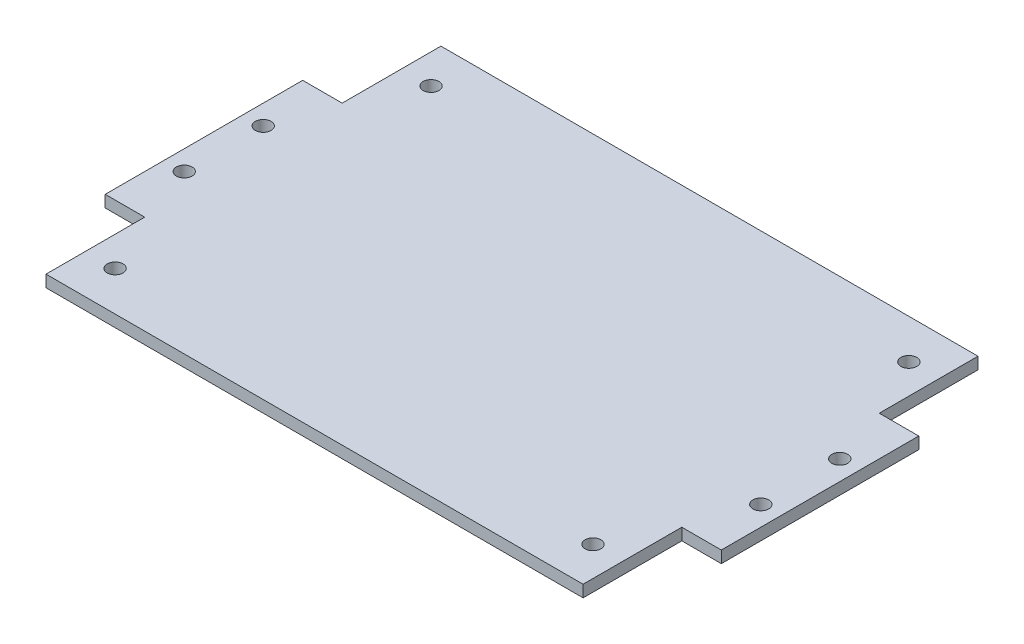
SolidWorks part; units mm, degrees
ref_plane "Plano frontal" through (0, 0, 0) normal (0, 0, 1) x (1, 0, 0)
ref_plane "Plano superior" through (0, 0, 0) normal (0, 1, 0) x (1, 0, 0)
ref_plane "Plano direito" through (0, 0, 0) normal (1, 0, 0) x (0, 0, -1)
sketch "Esboço2" plane through (0, 0, 0) normal (0, 1, 0) x (1, 0, 0)
  line L5 (-136, 100) -> (0, 100)
  line L6 (-136, 100) -> (-136, 0)
  line L7 (-136, 0) -> (0, 0)
  line L8 (0, 100) -> (0, 0)
extrude "Ressalto-extrusão1" add sketch "Esboço2" along normal blind 3
sketch "Esboço3" plane through (0, 3, 0) normal (0, 1, 0) x (1, 0, 0)
  circle A0 centre (-128.5, 10) radius 2
  circle A1 centre (-7.5, 10) radius 2
  circle A2 centre (-7.5, 90) radius 2
  circle A3 centre (-128.5, 90) radius 2
extrude "Corte-extrusão2" cut sketch "Esboço3" against normal blind 10
sketch "Esboço5" plane through (0, 0, 0) normal (1, 0, 0) x (0, 0, -1)
  line L0 (25, 0) -> (25, 3) construction
  line L1 (0, 0) -> (100, 0) construction
  line L2 (0, 3) -> (100, 3) construction
  line L3 (75, 0) -> (75, 3) construction
  line L4 (100, 3) -> (100, 0) construction
  line L5 (0, 3) -> (0, 0) construction
  line L7 (25, 0) -> (75, 0)
  line L8 (25, 0) -> (25, 3)
  line L9 (25, 3) -> (75, 3)
  line L10 (75, 0) -> (75, 3)
  dimension "D1" = 25
  dimension "D2" = 25
extrude "Ressalto-extrusão2" add sketch "Esboço5" along normal blind 10
sketch "Esboço6" plane through (-136, 0, 0) normal (-1, 0, 0) x (0, 0, 1)
  line L0 (-75, 3) -> (-75, 0) construction
  line L1 (-25, 0) -> (-25, 3) construction
  line L2 (-100, 0) -> (0, 0) construction
  line L3 (-100, 3) -> (0, 3) construction
  line L4 (-100, 3) -> (-100, 0) construction
  line L5 (0, 3) -> (0, 0) construction
  line L7 (-75, 0) -> (-25, 0)
  line L8 (-75, 0) -> (-75, 3)
  line L9 (-75, 3) -> (-25, 3)
  line L10 (-25, 0) -> (-25, 3)
  dimension "D1" = 25
  dimension "D2" = 25
extrude "Ressalto-extrusão3" add sketch "Esboço6" along normal blind 10
sketch "Esboço7" plane through (0, 3, 0) normal (0, 1, 0) x (1, 0, 0)
  line L0 (-141, 75) -> (-141, 25) construction
  line L1 (-146, 75) -> (-136, 75) construction
  line L2 (-146, 25) -> (-136, 25) construction
  line L3 (5, 75) -> (5, 25) construction
  line L4 (10, 75) -> (0, 75) construction
  line L5 (10, 25) -> (0, 25) construction
  line L6 (10, 40) -> (-146, 40) construction
  line L7 (10, 75) -> (10, 25) construction
  line L8 (-146, 25) -> (-146, 75) construction
  line L9 (-146, 60) -> (10, 60) construction
  circle A0 centre (5, 40) radius 2
  circle A1 centre (5, 60) radius 2
  circle A2 centre (-141, 60) radius 2
  circle A3 centre (-141, 40) radius 2
  dimension "D3" = 4
  dimension "D4" = 4
  dimension "D5" = 4
  dimension "D6" = 4
  dimension "D1" = 15
  dimension "D2" = 15
extrude "Corte-extrusão3" cut sketch "Esboço7" against normal blind 10
